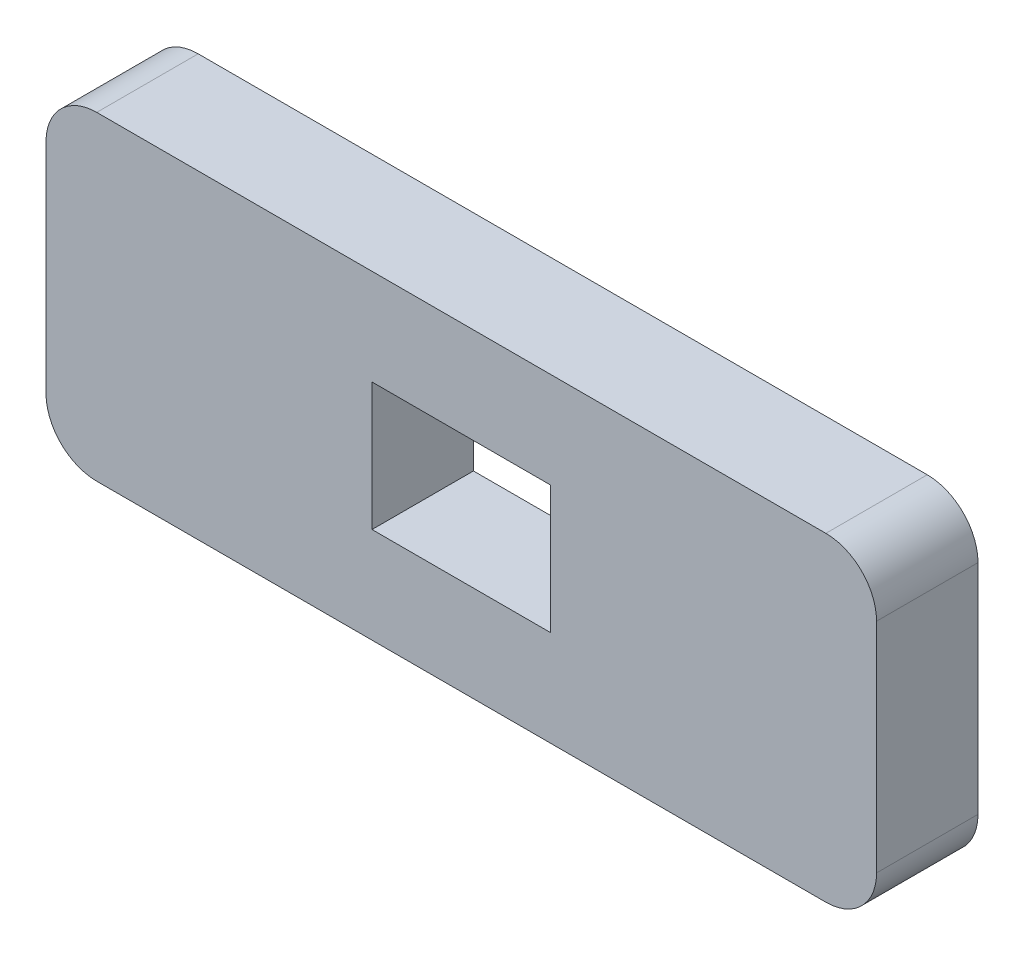
SolidWorks part; units mm, degrees
ref_plane "Front Plane" through (0, 0, 0) normal (0, 0, 1) x (1, 0, 0)
ref_plane "Top Plane" through (0, 0, 0) normal (0, 1, 0) x (1, 0, 0)
ref_plane "Right Plane" through (0, 0, 0) normal (1, 0, 0) x (0, 0, -1)
sketch "Sketch1" plane through (0, 0, 0) normal (0, 0, 1) x (1, 0, 0)
  line L1 (-5.706, -2.5) -> (5.706, -2.5)
  line L2 (-6.5, -1.706) -> (-6.5, 1.706)
  line L3 (-5.706, 2.5) -> (5.706, 2.5)
  line L4 (6.5, -1.706) -> (6.5, 1.706)
  line L5 (-6.5, -2.5) -> (6.5, 2.5) construction
  line L6 (-6.5, 2.5) -> (6.5, -2.5) construction
  arc A0 (5.706, 2.5) -> (6.5, 1.706) centre (5.706, 1.706) cw
  arc A1 (5.706, -2.5) -> (6.5, -1.706) centre (5.706, -1.706) ccw
  arc A2 (-5.706, -2.5) -> (-6.5, -1.706) centre (-5.706, -1.706) cw
  arc A3 (-6.5, 1.706) -> (-5.706, 2.5) centre (-5.706, 1.706) cw
  point P4 (0, 0)
  point P7 (6.5, 0)
  dimension "D3" = 0.794
  dimension "D1" = 13
  dimension "D2" = 5
extrude "Boss-Extrude1" add sketch "Sketch1" along normal blind 1.5875
sketch "Sketch2" plane through (0, 0, 1.5875) normal (0, 0, 1) x (1, 0, 0)
  line L1 (-1.397, -1) -> (1.397, -1)
  line L2 (-1.397, -1) -> (-1.397, 1)
  line L3 (-1.397, 1) -> (1.397, 1)
  line L4 (1.397, -1) -> (1.397, 1)
  line L5 (-1.397, -1) -> (1.397, 1) construction
  line L6 (-1.397, 1) -> (1.397, -1) construction
  point P4 (0, 0)
  dimension "D1" = 2
  dimension "D2" = 2.794
extrude "Cut-Extrude1" cut sketch "Sketch2" against normal through all
